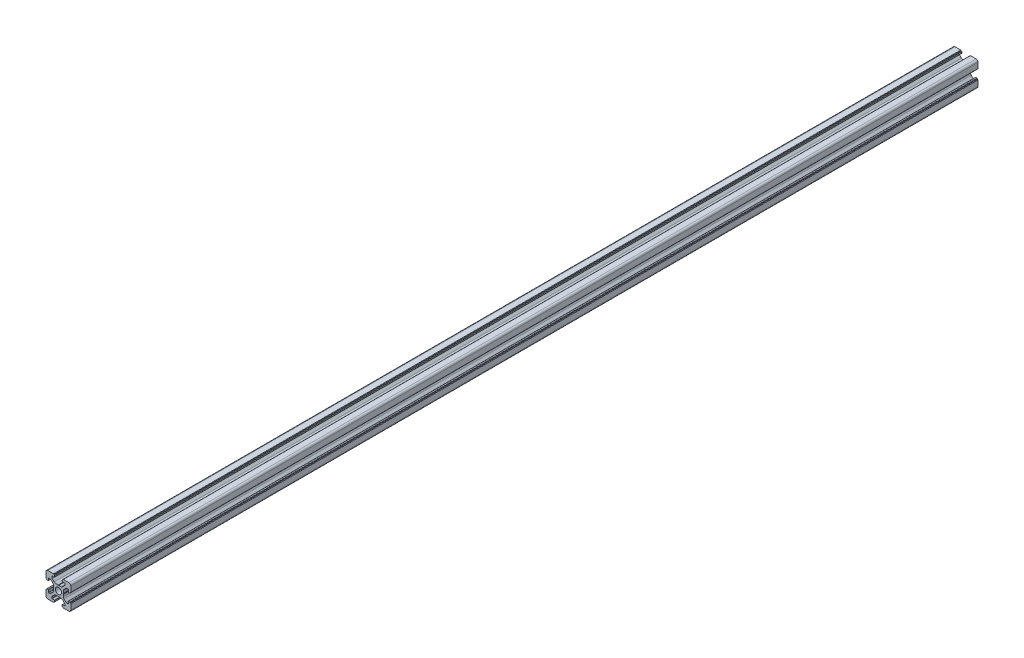
SolidWorks part; units mm, degrees
ref_plane "Спереди" through (0, 0, 0) normal (0, 0, 1) x (1, 0, 0)
ref_plane "Сверху" through (0, 0, 0) normal (0, 1, 0) x (1, 0, 0)
ref_plane "Справа" through (0, 0, 0) normal (1, 0, 0) x (0, 0, -1)
sketch "Эскиз1" plane through (0, 0, 0) normal (0, 0, 1) x (1, 0, 0)
  line L144 (-3.8, 0) -> (-3.9452, -0.1815)
  line L145 (-3.9452, 0.1815) -> (-3.8, 0)
  line L146 (-4, 1.9341) -> (-4, 0.3377)
  line L147 (-6.1445, 4.9071) -> (-4.5858, 3.3483)
  line L148 (-7.8, 5.2) -> (-6.8517, 5.2)
  line L149 (-8, 3.32) -> (-8, 5)
  line L150 (-9.15, 3.07) -> (-8.25, 3.07)
  line L151 (-9.4, 3.7) -> (-9.4, 3.32)
  line L152 (-9.75, 3.7) -> (-9.4, 3.7)
  line L153 (-10, 8.5) -> (-10, 3.95)
  line L154 (-3.95, 10) -> (-8.5, 10)
  line L155 (-3.7, 9.4) -> (-3.7, 9.75)
  line L156 (-3.32, 9.4) -> (-3.7, 9.4)
  line L157 (-3.07, 8.25) -> (-3.07, 9.15)
  line L158 (-5, 8) -> (-3.32, 8)
  line L159 (-5.2, 6.8517) -> (-5.2, 7.8)
  line L160 (-3.3483, 4.5858) -> (-4.9071, 6.1445)
  line L161 (-0.3377, 4) -> (-1.9341, 4)
  line L162 (0, 3.8) -> (-0.1815, 3.9452)
  line L163 (0.1815, 3.9452) -> (0, 3.8)
  line L164 (1.9341, 4) -> (0.3377, 4)
  line L165 (4.9071, 6.1445) -> (3.3483, 4.5858)
  line L166 (5.2, 7.8) -> (5.2, 6.8517)
  line L167 (3.32, 8) -> (5, 8)
  line L168 (3.07, 9.15) -> (3.07, 8.25)
  line L169 (3.7, 9.4) -> (3.32, 9.4)
  line L170 (3.7, 9.75) -> (3.7, 9.4)
  line L171 (8.5, 10) -> (3.95, 10)
  line L172 (10, 3.95) -> (10, 8.5)
  line L173 (9.4, 3.7) -> (9.75, 3.7)
  line L174 (9.4, 3.32) -> (9.4, 3.7)
  line L175 (8.25, 3.07) -> (9.15, 3.07)
  line L176 (8, 5) -> (8, 3.32)
  line L177 (6.8517, 5.2) -> (7.8, 5.2)
  line L178 (4.5858, 3.3483) -> (6.1445, 4.9071)
  line L179 (4, 0.3377) -> (4, 1.9341)
  line L180 (3.8, 0) -> (3.9452, 0.1815)
  line L181 (3.9452, -0.1815) -> (3.8, 0)
  line L182 (4, -1.9341) -> (4, -0.3377)
  line L183 (6.1445, -4.9071) -> (4.5858, -3.3483)
  line L184 (7.8, -5.2) -> (6.8517, -5.2)
  line L185 (8, -3.32) -> (8, -5)
  line L186 (9.15, -3.07) -> (8.25, -3.07)
  line L187 (9.4, -3.7) -> (9.4, -3.32)
  line L188 (9.75, -3.7) -> (9.4, -3.7)
  line L189 (10, -8.5) -> (10, -3.95)
  line L190 (3.95, -10) -> (8.5, -10)
  line L191 (3.7, -9.4) -> (3.7, -9.75)
  line L192 (3.32, -9.4) -> (3.7, -9.4)
  line L193 (3.07, -8.25) -> (3.07, -9.15)
  line L194 (5, -8) -> (3.32, -8)
  line L195 (5.2, -6.8517) -> (5.2, -7.8)
  line L196 (3.3483, -4.5858) -> (4.9071, -6.1445)
  line L197 (0.3377, -4) -> (1.9341, -4)
  line L198 (0, -3.8) -> (0.1815, -3.9452)
  line L199 (-0.1815, -3.9452) -> (0, -3.8)
  line L200 (-1.9341, -4) -> (-0.3377, -4)
  line L201 (-4.9071, -6.1445) -> (-3.3483, -4.5858)
  line L202 (-5.2, -7.8) -> (-5.2, -6.8517)
  line L203 (-3.32, -8) -> (-5, -8)
  line L204 (-3.07, -9.15) -> (-3.07, -8.25)
  line L205 (-3.7, -9.4) -> (-3.32, -9.4)
  line L206 (-3.7, -9.75) -> (-3.7, -9.4)
  line L207 (-8.5, -10) -> (-3.95, -10)
  line L208 (-10, -3.95) -> (-10, -8.5)
  line L209 (-9.4, -3.7) -> (-9.75, -3.7)
  line L210 (-9.4, -3.32) -> (-9.4, -3.7)
  line L211 (-8.25, -3.07) -> (-9.15, -3.07)
  line L212 (-8, -5) -> (-8, -3.32)
  line L213 (-6.8517, -5.2) -> (-7.8, -5.2)
  line L214 (-4.5858, -3.3483) -> (-6.1445, -4.9071)
  line L215 (-4, -0.3377) -> (-4, -1.9341)
  arc A2 (2.5, 0) -> (-2.5, 0) centre (0, 0) ccw
  arc A3 (-2.5, 0) -> (2.5, 0) centre (0, 0) ccw
  arc A120 (-4, 0.3377) -> (-3.9452, 0.1815) centre (-3.75, 0.3377) ccw
  arc A121 (-4, 1.9341) -> (-4.5858, 3.3483) centre (-6, 1.9341) ccw
  arc A122 (-6.1445, 4.9071) -> (-6.8517, 5.2) centre (-6.8517, 4.2) ccw
  arc A123 (-7.8, 5.2) -> (-8, 5) centre (-7.8, 5) ccw
  arc A124 (-8.25, 3.07) -> (-8, 3.32) centre (-8.25, 3.32) ccw
  arc A125 (-9.4, 3.32) -> (-9.15, 3.07) centre (-9.15, 3.32) ccw
  arc A126 (-10, 3.95) -> (-9.75, 3.7) centre (-9.75, 3.95) ccw
  arc A127 (-8.5, 10) -> (-10, 8.5) centre (-8.5, 8.5) ccw
  arc A128 (-3.7, 9.75) -> (-3.95, 10) centre (-3.95, 9.75) ccw
  arc A129 (-3.07, 9.15) -> (-3.32, 9.4) centre (-3.32, 9.15) ccw
  arc A130 (-3.32, 8) -> (-3.07, 8.25) centre (-3.32, 8.25) ccw
  arc A131 (-5, 8) -> (-5.2, 7.8) centre (-5, 7.8) ccw
  arc A132 (-5.2, 6.8517) -> (-4.9071, 6.1445) centre (-4.2, 6.8517) ccw
  arc A133 (-3.3483, 4.5858) -> (-1.9341, 4) centre (-1.9341, 6) ccw
  arc A134 (-0.1815, 3.9452) -> (-0.3377, 4) centre (-0.3377, 3.75) ccw
  arc A135 (0.3377, 4) -> (0.1815, 3.9452) centre (0.3377, 3.75) ccw
  arc A136 (1.9341, 4) -> (3.3483, 4.5858) centre (1.9341, 6) ccw
  arc A137 (4.9071, 6.1445) -> (5.2, 6.8517) centre (4.2, 6.8517) ccw
  arc A138 (5.2, 7.8) -> (5, 8) centre (5, 7.8) ccw
  arc A139 (3.07, 8.25) -> (3.32, 8) centre (3.32, 8.25) ccw
  arc A140 (3.32, 9.4) -> (3.07, 9.15) centre (3.32, 9.15) ccw
  arc A141 (3.95, 10) -> (3.7, 9.75) centre (3.95, 9.75) ccw
  arc A142 (10, 8.5) -> (8.5, 10) centre (8.5, 8.5) ccw
  arc A143 (9.75, 3.7) -> (10, 3.95) centre (9.75, 3.95) ccw
  arc A144 (9.15, 3.07) -> (9.4, 3.32) centre (9.15, 3.32) ccw
  arc A145 (8, 3.32) -> (8.25, 3.07) centre (8.25, 3.32) ccw
  arc A146 (8, 5) -> (7.8, 5.2) centre (7.8, 5) ccw
  arc A147 (6.8517, 5.2) -> (6.1445, 4.9071) centre (6.8517, 4.2) ccw
  arc A148 (4.5858, 3.3483) -> (4, 1.9341) centre (6, 1.9341) ccw
  arc A149 (3.9452, 0.1815) -> (4, 0.3377) centre (3.75, 0.3377) ccw
  arc A150 (4, -0.3377) -> (3.9452, -0.1815) centre (3.75, -0.3377) ccw
  arc A151 (4, -1.9341) -> (4.5858, -3.3483) centre (6, -1.9341) ccw
  arc A152 (6.1445, -4.9071) -> (6.8517, -5.2) centre (6.8517, -4.2) ccw
  arc A153 (7.8, -5.2) -> (8, -5) centre (7.8, -5) ccw
  arc A154 (8.25, -3.07) -> (8, -3.32) centre (8.25, -3.32) ccw
  arc A155 (9.4, -3.32) -> (9.15, -3.07) centre (9.15, -3.32) ccw
  arc A156 (10, -3.95) -> (9.75, -3.7) centre (9.75, -3.95) ccw
  arc A157 (8.5, -10) -> (10, -8.5) centre (8.5, -8.5) ccw
  arc A158 (3.7, -9.75) -> (3.95, -10) centre (3.95, -9.75) ccw
  arc A159 (3.07, -9.15) -> (3.32, -9.4) centre (3.32, -9.15) ccw
  arc A160 (3.32, -8) -> (3.07, -8.25) centre (3.32, -8.25) ccw
  arc A161 (5, -8) -> (5.2, -7.8) centre (5, -7.8) ccw
  arc A162 (5.2, -6.8517) -> (4.9071, -6.1445) centre (4.2, -6.8517) ccw
  arc A163 (3.3483, -4.5858) -> (1.9341, -4) centre (1.9341, -6) ccw
  arc A164 (0.1815, -3.9452) -> (0.3377, -4) centre (0.3377, -3.75) ccw
  arc A165 (-0.3377, -4) -> (-0.1815, -3.9452) centre (-0.3377, -3.75) ccw
  arc A166 (-1.9341, -4) -> (-3.3483, -4.5858) centre (-1.9341, -6) ccw
  arc A167 (-4.9071, -6.1445) -> (-5.2, -6.8517) centre (-4.2, -6.8517) ccw
  arc A168 (-5.2, -7.8) -> (-5, -8) centre (-5, -7.8) ccw
  arc A169 (-3.07, -8.25) -> (-3.32, -8) centre (-3.32, -8.25) ccw
  arc A170 (-3.32, -9.4) -> (-3.07, -9.15) centre (-3.32, -9.15) ccw
  arc A171 (-3.95, -10) -> (-3.7, -9.75) centre (-3.95, -9.75) ccw
  arc A172 (-10, -8.5) -> (-8.5, -10) centre (-8.5, -8.5) ccw
  arc A173 (-9.75, -3.7) -> (-10, -3.95) centre (-9.75, -3.95) ccw
  arc A174 (-9.15, -3.07) -> (-9.4, -3.32) centre (-9.15, -3.32) ccw
  arc A175 (-8, -3.32) -> (-8.25, -3.07) centre (-8.25, -3.32) ccw
  arc A176 (-8, -5) -> (-7.8, -5.2) centre (-7.8, -5) ccw
  arc A177 (-6.8517, -5.2) -> (-6.1445, -4.9071) centre (-6.8517, -4.2) ccw
  arc A178 (-4.5858, -3.3483) -> (-4, -1.9341) centre (-6, -1.9341) ccw
  arc A179 (-3.9452, -0.1815) -> (-4, -0.3377) centre (-3.75, -0.3377) ccw
extrude "Бобышка-Вытянуть1" add sketch "Эскиз1" along normal blind 732
